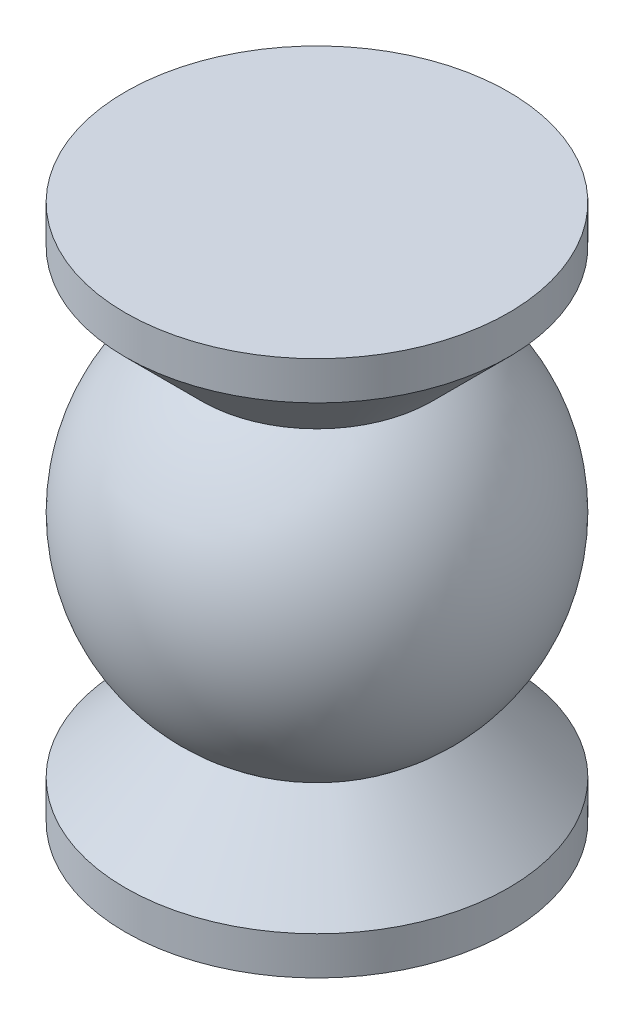
SolidWorks part; units mm, degrees
ref_plane "前视基准面" through (0, 0, 0) normal (0, 0, 1) x (1, 0, 0)
ref_plane "上视基准面" through (0, 0, 0) normal (0, 1, 0) x (1, 0, 0)
ref_plane "右视基准面" through (0, 0, 0) normal (1, 0, 0) x (0, 0, -1)
other "Configuration Table"
sketch "草图1" plane through (0, 0, 0) normal (0, 0, 1) x (1, 0, 0)
  line L0 (0, 52.3743) -> (0, -48.3457) construction
  line L1 (0, 35) -> (25, 35)
  line L2 (25, 35) -> (25, 30)
  line L3 (25, 30) -> (15, 20)
  line L4 (-29.5266, 0) -> (47.3624, 0) construction
  line L5 (0, -35) -> (25, -35)
  line L6 (25, -35) -> (25, -30)
  line L7 (25, -30) -> (15, -20)
  line L8 (0, 35) -> (0, -35)
  arc A0 (15, 20) -> (15, -20) centre (0, 0) cw
  dimension "D1" = 40
  dimension "D2" = 5
  dimension "D3" = 50
  dimension "D4" = 70
  dimension "D5" = 45
revolve "旋转1" add sketch "草图1" angle 360 about L0
